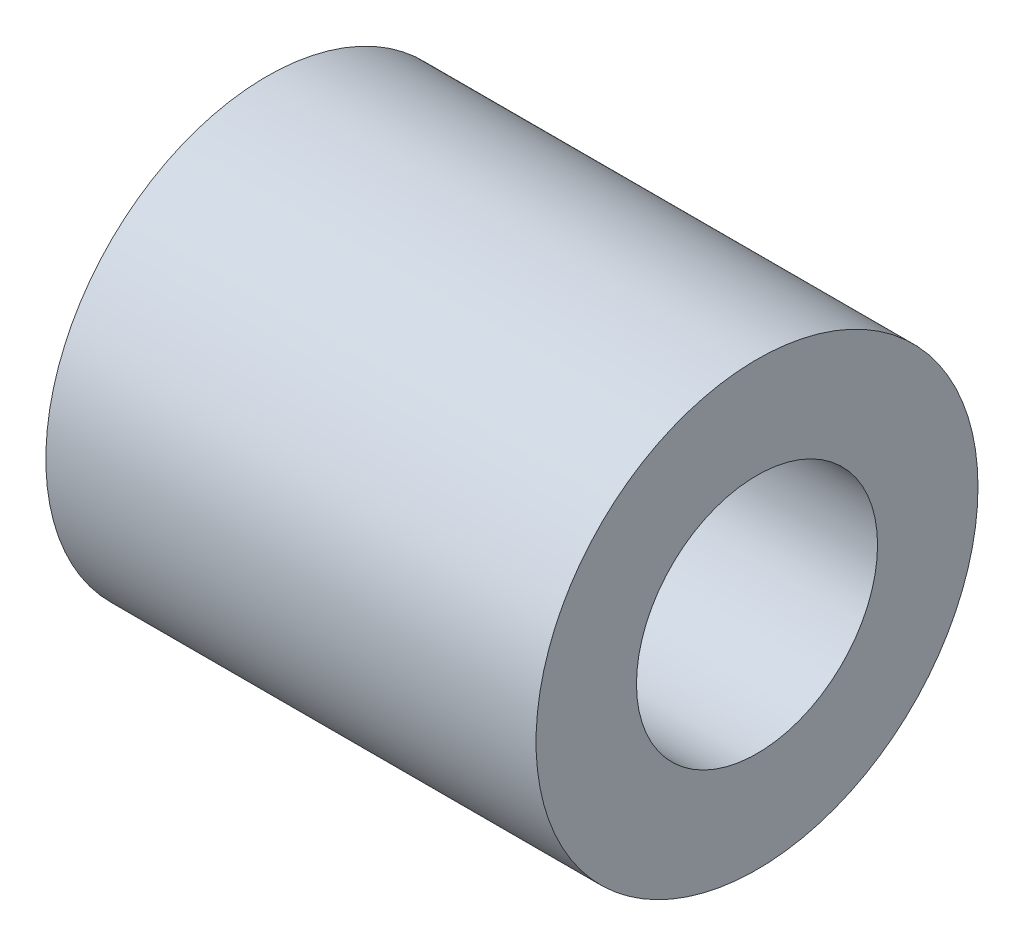
SolidWorks part; units mm, degrees
ref_plane "前视基准面" through (0, 0, 0) normal (0, 0, 1) x (1, 0, 0)
ref_plane "上视基准面" through (0, 0, 0) normal (0, 1, 0) x (1, 0, 0)
ref_plane "右视基准面" through (0, 0, 0) normal (1, 0, 0) x (0, 0, -1)
sketch "草图1" plane through (0, 0, 0) normal (1, 0, 0) x (0, 0, -1)
  circle A0 centre (0, 0) radius 3
  circle A1 centre (0, 0) radius 5.5
extrude "凸台-拉伸1" add sketch "草图1" along normal blind 12.2
